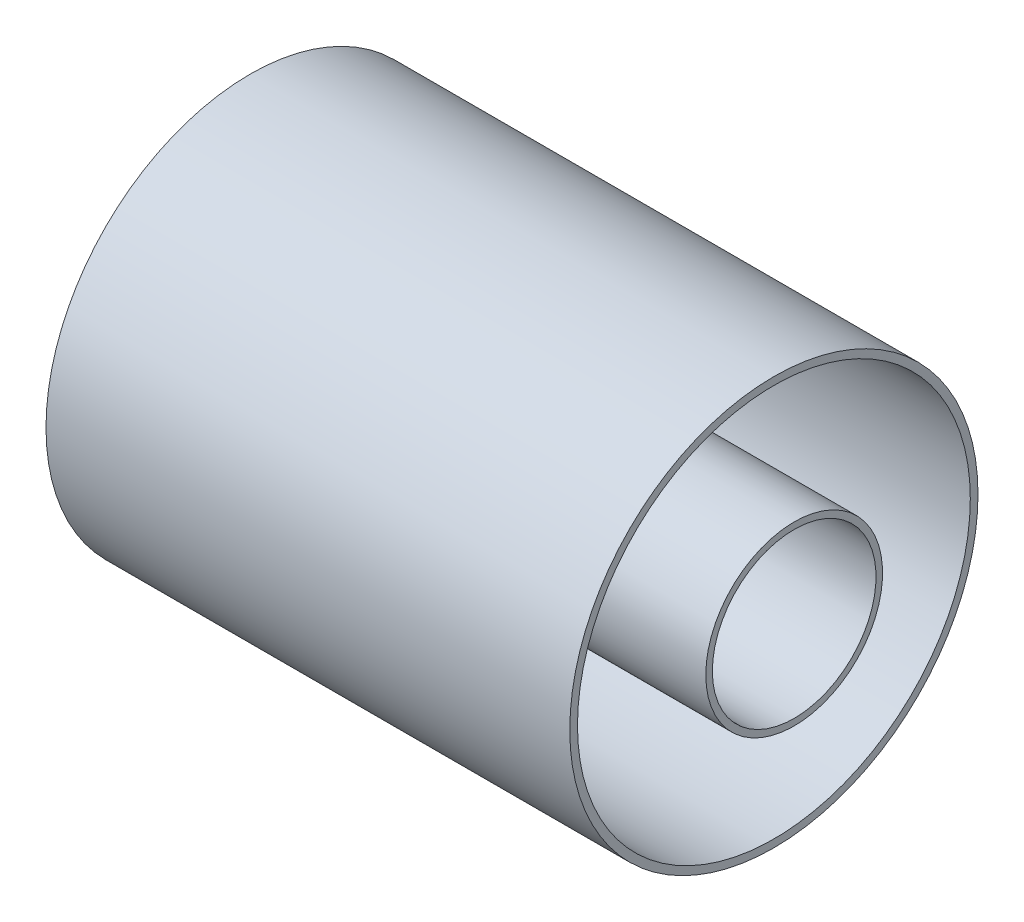
SolidWorks part; units mm, degrees
ref_plane "Front Plane" through (0, 0, 0) normal (0, 0, 1) x (1, 0, 0)
ref_plane "Top Plane" through (0, 0, 0) normal (0, 1, 0) x (1, 0, 0)
ref_plane "Right Plane" through (0, 0, 0) normal (1, 0, 0) x (0, 0, -1)
sketch "Sketch2" plane through (0, 0, 0) normal (0, 0, 1) x (1, 0, 0)
  line L0 (0, 0) -> (51.3521, 0)
  line L1 (-154.984, 31.75) -> (60.154, 31.75)
  line L2 (-154.984, 34.29) -> (60.154, 34.29)
  line L3 (-150.92, 76.2) -> (52.28, 76.2)
  line L4 (-150.92, 79.1845) -> (52.28, 79.1845)
  line L5 (52.28, 79.1845) -> (52.28, 76.2)
  line L6 (-150.92, 79.1845) -> (-150.92, 76.2)
  line L7 (-154.984, 34.29) -> (-154.984, 31.75)
  line L8 (60.154, 34.29) -> (60.154, 31.75)
  dimension "D1" = 2.54
  dimension "D2" = 2.9845
  dimension "D3" = 31.75
  dimension "D4" = 76.2
  dimension "D5" = 215.138
  dimension "D6" = 203.2
  dimension "D7" = 4.064
revolve "Revolve1" add sketch "Sketch2" angle 360 about L0
